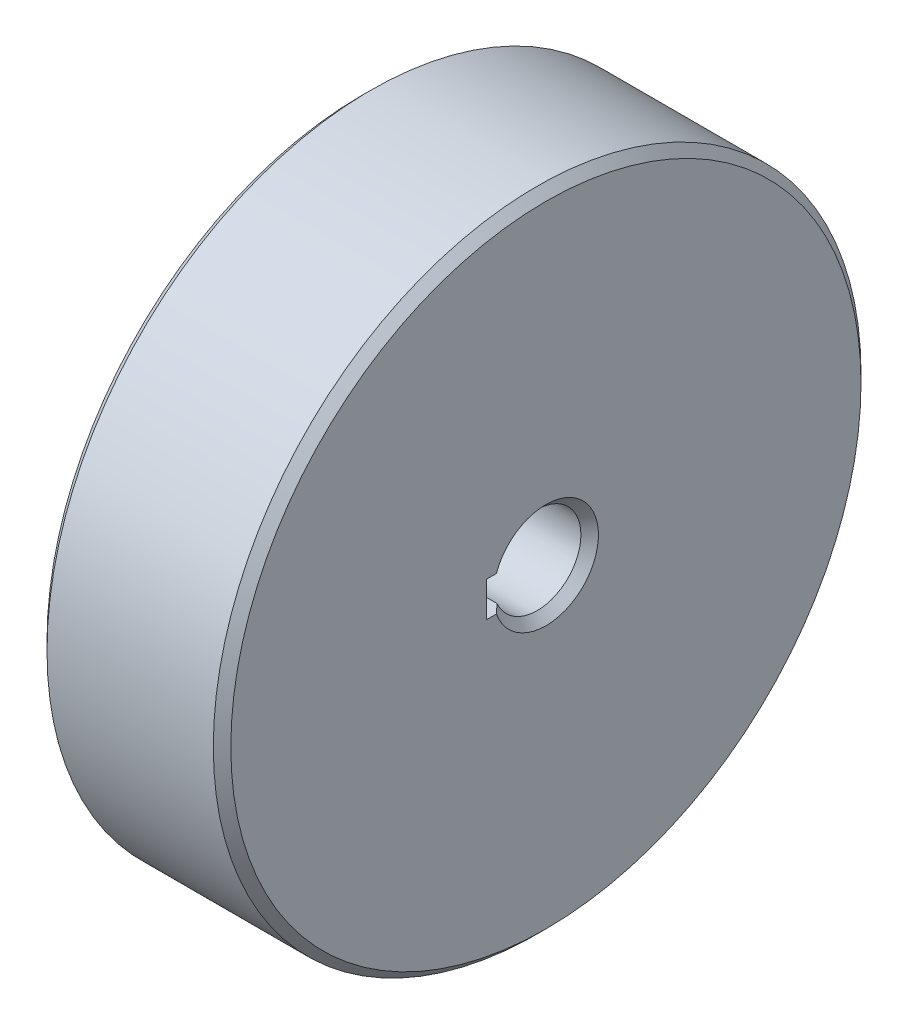
SolidWorks part; units mm, degrees
ref_plane "Front" through (0, 0, 0) normal (0, 0, 1) x (1, 0, 0)
ref_plane "Top" through (0, 0, 0) normal (0, 1, 0) x (1, 0, 0)
ref_plane "Right" through (0, 0, 0) normal (1, 0, 0) x (0, 0, -1)
sketch "Sketch1" plane through (0, 0, 0) normal (0, 1, 0) x (1, 0, 0)
  line L0 (0, 0) -> (21, 0) construction
  line L1 (0, -37) -> (21, -37)
  line L2 (0, -37) -> (0, -5)
  line L3 (0, -5) -> (21, -5)
  line L4 (21, -37) -> (21, -5)
  dimension "D1" = 74
  dimension "D2" = 10
  dimension "D3" = 21
revolve "Revolve1" add sketch "Sketch1" angle 360 about L0
sketch "Sketch2" plane through (0, 0, 0) normal (1, 0, 0) x (0, 0, -1)
  line L1 (-4.5826, -2) -> (-6.8, -2)
  line L3 (-4.5826, 2) -> (-6.8, 2)
  line L4 (-6.8, -2) -> (-6.8, 2)
  circle A0 centre (0, 0) radius 5 construction
  arc A1 (-4.5826, 2) -> (-4.5826, -2) centre (0, 0) ccw
  dimension "D1" = 4
  dimension "D2" = 6.8
extrude "Cut-Extrude2" cut sketch "Sketch2" along normal through all
chamfer "Chamfer1" distance 1 angle 45 4 edges at (0, 0, -5) (21, 0, -5) (0, 0, 37) (21, 0, 37)
